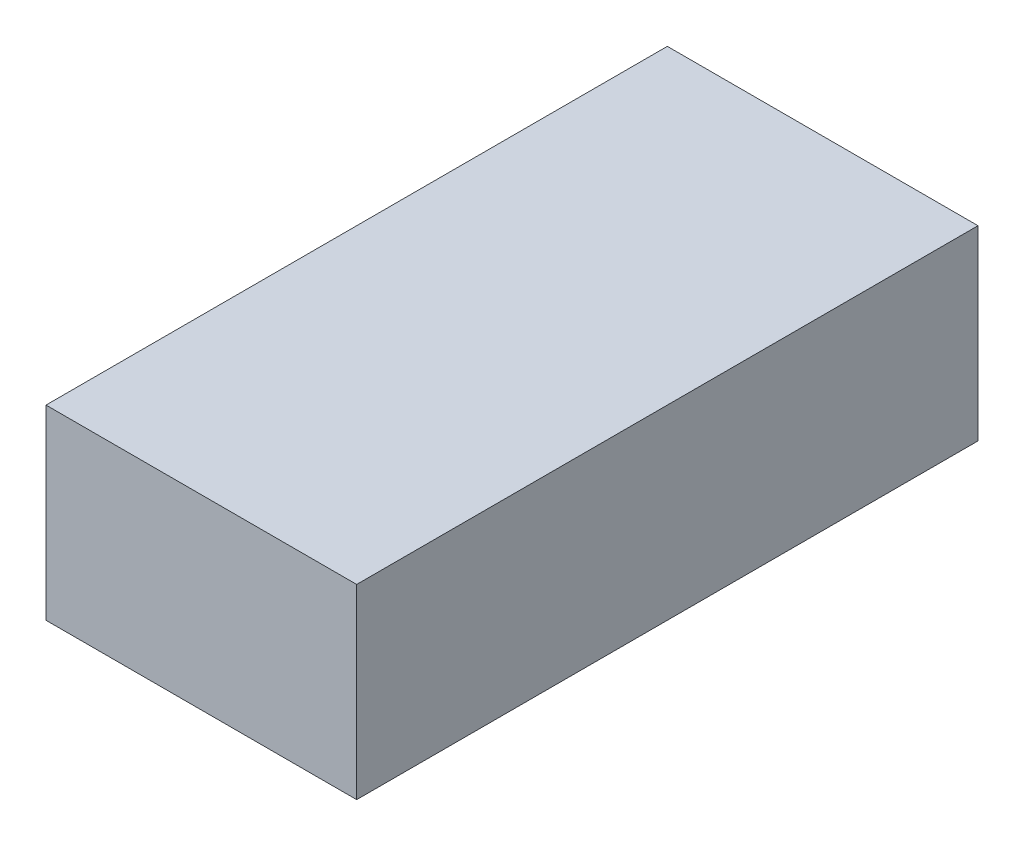
SolidWorks part; units mm, degrees
material "ABS"
ref_plane "Alzado" through (0, 0, 0) normal (0, 0, 1) x (1, 0, 0)
ref_plane "Planta" through (0, 0, 0) normal (0, 1, 0) x (1, 0, 0)
ref_plane "Vista lateral" through (0, 0, 0) normal (1, 0, 0) x (0, 0, -1)
sketch "Croquis1" plane through (0, 0, 0) normal (0, 0, 1) x (1, 0, 0)
  line L1 (-12.5, 7.5) -> (12.5, 7.5)
  line L2 (-12.5, 7.5) -> (-12.5, -7.5)
  line L3 (-12.5, -7.5) -> (12.5, -7.5)
  line L4 (12.5, 7.5) -> (12.5, -7.5)
  line L5 (-12.5, 7.5) -> (12.5, -7.5) construction
  line L6 (-12.5, -7.5) -> (12.5, 7.5) construction
  point P0 (0, 0)
  dimension "D1" = 25
  dimension "D2" = 15
extrude "Saliente-Extruir1" add sketch "Croquis1" along normal blind 50
